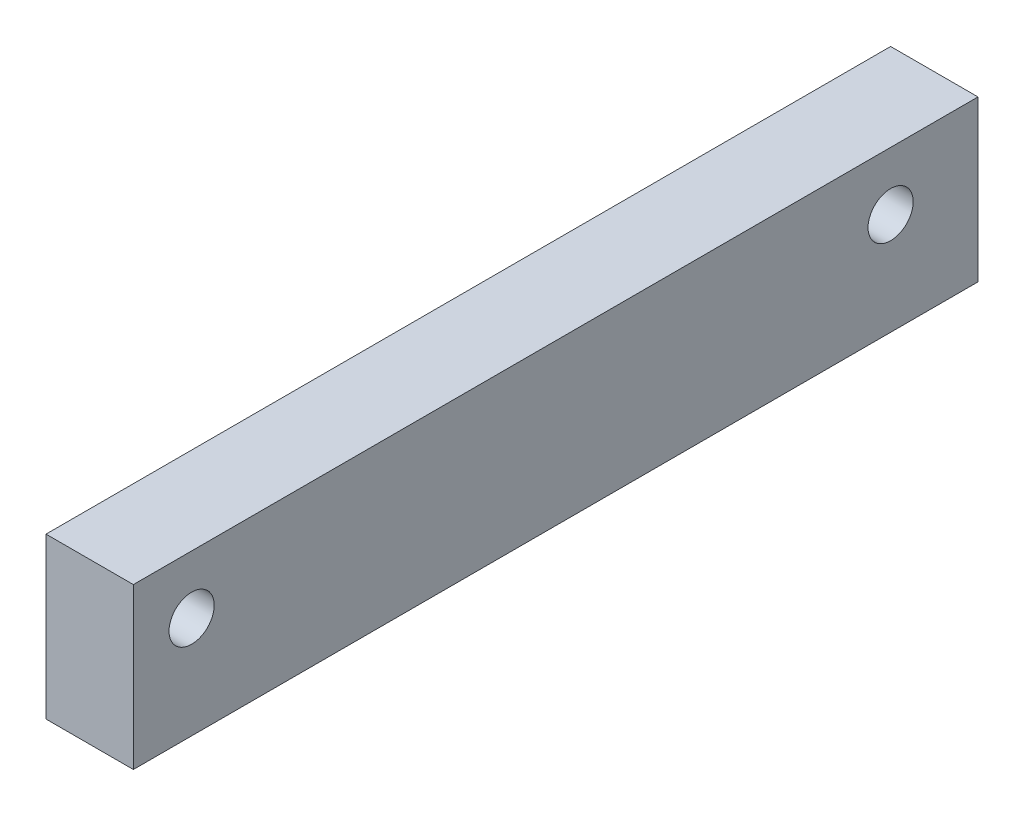
SolidWorks part; units mm, degrees
ref_plane "Płaszczyzna przednia" through (0, 0, 0) normal (0, 0, 1) x (1, 0, 0)
ref_plane "Płaszczyzna górna" through (0, 0, 0) normal (0, 1, 0) x (1, 0, 0)
ref_plane "Płaszczyzna prawa" through (0, 0, 0) normal (1, 0, 0) x (0, 0, -1)
sketch "Szkic1" plane through (0, 0, 0) normal (-1, 0, 0) x (0, 0, 1)
  line L0 (-817, 29.6923) -> (-817, 40.6923)
  line L2 (-875, 29.6923) -> (-817, 29.6923)
  line L4 (-817, 40.6923) -> (-875, 40.6923)
  line L5 (-875, 40.6923) -> (-875, 32.6923)
  line L6 (-875, 32.6923) -> (-817, 32.6923)
  line L7 (-817, 32.6923) -> (-817, 40.6923)
  line L8 (-817, 40.6923) -> (-875, 40.6923)
  line L9 (-875, 40.6923) -> (-875, 29.6923)
  circle A0 centre (-869, 36.6923) radius 1.55 construction
  circle A1 centre (-821, 36.6923) radius 1.55 construction
  circle A2 centre (-869, 36.6923) radius 1.55
  circle A3 centre (-821, 36.6923) radius 1.55
  dimension "D1" = 0
extrude "Dodanie-wyciągnięcie1" add sketch "Szkic1" along normal blind 6
